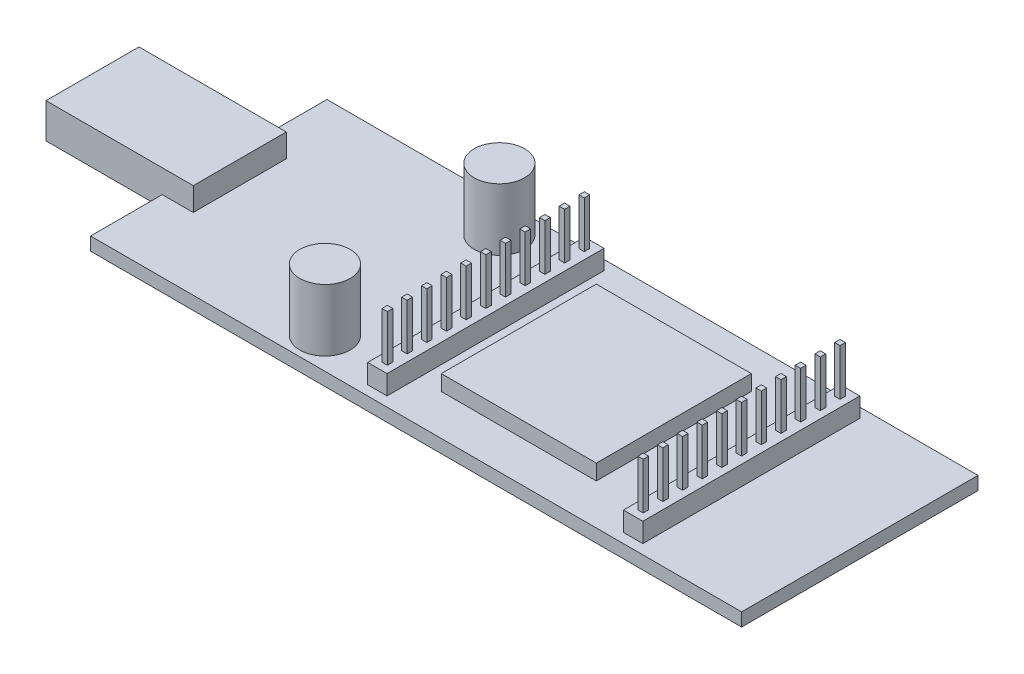
SolidWorks part; units mm, degrees
ref_plane "Front Plane" through (0, 0, 0) normal (0, 0, 1) x (1, 0, 0)
ref_plane "Top Plane" through (0, 0, 0) normal (0, 1, 0) x (1, 0, 0)
ref_plane "Right Plane" through (0, 0, 0) normal (1, 0, 0) x (0, 0, -1)
sketch "Sketch1" plane through (0, 0, 0) normal (0, 1, 0) x (1, 0, 0)
  line L1 (-42, 15.25) -> (42, 15.25)
  line L2 (-42, 15.25) -> (-42, -15.25)
  line L3 (-42, -15.25) -> (42, -15.25)
  line L4 (42, 15.25) -> (42, -15.25)
  line L5 (-42, 15.25) -> (42, -15.25) construction
  line L6 (-42, -15.25) -> (42, 15.25) construction
  point P0 (0, 0)
  dimension "D1" = 84
  dimension "D2" = 30.5
extrude "Boss-Extrude1" add sketch "Sketch1" along normal blind 1.7
sketch "Sketch2" plane through (0, 1.7, 0) normal (0, 1, 0) x (1, 0, 0)
  line L0 (-42, 0) -> (-53.9187, 0) construction
  line L1 (-42, 15.25) -> (-42, -15.25) construction
  line L3 (-57, -6) -> (-38, -6)
  line L4 (-57, -6) -> (-57, 6)
  line L5 (-57, 6) -> (-38, 6)
  line L6 (-38, -6) -> (-38, 6)
  line L7 (-57, -6) -> (-38, 6) construction
  line L8 (-57, 6) -> (-38, -6) construction
  point P5 (-47.5, 0)
  dimension "D1" = 12
  dimension "D2" = 19
  dimension "D3" = 15
extrude "Boss-Extrude2" add sketch "Sketch2" along normal blind 3 and the other way blind 1.5
sketch "Sketch3" plane through (0, 1.7, 0) normal (0, 1, 0) x (1, 0, 0)
  line L0 (0, 0) -> (42, 0) construction
  line L1 (42, -15.25) -> (42, 15.25) construction
  line L3 (-2, -10) -> (18, -10)
  line L4 (-2, -10) -> (-2, 10)
  line L5 (-2, 10) -> (18, 10)
  line L6 (18, -10) -> (18, 10)
  line L7 (-2, -10) -> (18, 10) construction
  line L8 (-2, 10) -> (18, -10) construction
  point P5 (8, 0)
  dimension "D1" = 20
  dimension "D2" = 20
  dimension "D3" = 34
extrude "Boss-Extrude3" add sketch "Sketch3" along normal blind 2
sketch "Sketch4" plane through (0, 0, 0) normal (0, -1, 0) x (1, 0, 0)
  line L1 (-36.2017, 11.8652) -> (-30.5739, 11.8652)
  line L2 (-36.2017, 11.8652) -> (-36.2017, 6.894)
  line L3 (-36.2017, 6.894) -> (-30.5739, 6.894)
  line L4 (-30.5739, 11.8652) -> (-30.5739, 6.894)
  line L5 (-36.2017, 11.8652) -> (-30.5739, 6.894) construction
  line L6 (-36.2017, 6.894) -> (-30.5739, 11.8652) construction
  line L7 (-26.1186, -0.7973) -> (-16.4576, -0.7973)
  line L8 (-26.1186, -0.7973) -> (-26.1186, -5.2995)
  line L9 (-26.1186, -5.2995) -> (-16.4576, -5.2995)
  line L10 (-16.4576, -0.7973) -> (-16.4576, -5.2995)
  line L11 (-26.1186, -0.7973) -> (-16.4576, -5.2995) construction
  line L12 (-26.1186, -5.2995) -> (-16.4576, -0.7973) construction
  line L13 (10.8372, 12.4749) -> (20.3106, 12.4749)
  line L14 (10.8372, 12.4749) -> (10.8372, 3.8456)
  line L15 (10.8372, 3.8456) -> (20.3106, 3.8456)
  line L16 (20.3106, 12.4749) -> (20.3106, 3.8456)
  line L17 (10.8372, 12.4749) -> (20.3106, 3.8456) construction
  line L18 (10.8372, 3.8456) -> (20.3106, 12.4749) construction
  line L19 (4.8342, -0.8911) -> (14.7766, -0.8911)
  line L20 (4.8342, -0.8911) -> (4.8342, -8.3948)
  line L21 (4.8342, -8.3948) -> (14.7766, -8.3948)
  line L22 (14.7766, -0.8911) -> (14.7766, -8.3948)
  line L23 (4.8342, -0.8911) -> (14.7766, -8.3948) construction
  line L24 (4.8342, -8.3948) -> (14.7766, -0.8911) construction
  point P0 (-33.3878, 9.3796)
  point P5 (-21.2881, -3.0484)
  point P10 (15.5739, 8.1603)
  point P15 (9.8054, -4.6429)
extrude "Boss-Extrude4" add sketch "Sketch4" along normal blind 2
sketch "Sketch5" plane through (0, 1.7, 0) normal (0, 1, 0) x (1, 0, 0)
  line L0 (-15.7541, 15.25) -> (-15.7541, -15.25) construction
  line L1 (42, 15.25) -> (-42, 15.25) construction
  line L2 (-42, -15.25) -> (42, -15.25) construction
  line L3 (-19.0369, 0) -> (-11.9553, 0) construction
  circle A0 centre (-15.7541, 11.25) radius 3.25
  circle A1 centre (-15.7541, -11.25) radius 3.25
  dimension "D1" = 6.5
  dimension "D2" = 4
extrude "Boss-Extrude5" add sketch "Sketch5" along normal blind 8
sketch "Sketch6" plane through (0, 1.7, 0) normal (0, 1, 0) x (1, 0, 0)
  line L0 (-41.6888, 0) -> (42, 0) construction
  line L1 (42, -15.25) -> (42, 15.25) construction
  line L3 (-7.5, -14) -> (-5, -14)
  line L4 (-7.5, -14) -> (-7.5, 14)
  line L5 (-7.5, 14) -> (-5, 14)
  line L6 (-5, -14) -> (-5, 14)
  line L7 (-7.5, -14) -> (-5, 14) construction
  line L8 (-7.5, 14) -> (-5, -14) construction
  line L9 (25.5, -14) -> (28, -14)
  line L10 (25.5, -14) -> (25.5, 14)
  line L11 (25.5, 14) -> (28, 14)
  line L12 (28, -14) -> (28, 14)
  line L13 (25.5, -14) -> (28, 14) construction
  line L14 (25.5, 14) -> (28, -14) construction
  point P4 (-6.25, 0)
  point P9 (26.75, 0)
  dimension "D1" = 2.5
  dimension "D2" = 2.5
  dimension "D3" = 28
  dimension "D4" = 28
  dimension "D5" = 14
  dimension "D6" = 47
extrude "Boss-Extrude6" add sketch "Sketch6" along normal blind 2.5
sketch "Sketch7" plane through (0, 4.2, 0) normal (0, 1, 0) x (1, 0, 0)
  line L0 (-6.25, 14) -> (-6.25, -14) construction
  line L1 (-5, 14) -> (-7.5, 14) construction
  line L2 (-7.5, -14) -> (-5, -14) construction
  line L3 (-7.5, 0) -> (-5, 0) construction
  line L4 (-7.5, 14) -> (-7.5, -14) construction
  line L5 (-5, -14) -> (-5, 14) construction
  line L6 (-6.6, 2.89) -> (-6.6, 2.19)
  line L7 (-6.6, 0.35) -> (-5.9, 0.35)
  line L8 (-6.6, 0.35) -> (-6.6, -0.35)
  line L9 (-6.6, -0.35) -> (-5.9, -0.35)
  line L10 (-5.9, 0.35) -> (-5.9, -0.35)
  line L11 (-6.6, 0.35) -> (-5.9, -0.35) construction
  line L12 (-6.6, -0.35) -> (-5.9, 0.35) construction
  line L13 (-6.6, 2.89) -> (-5.9, 2.89)
  line L14 (-5.9, 2.89) -> (-5.9, 2.19)
  line L15 (-6.6, 2.19) -> (-5.9, 2.19)
  line L16 (-6.6, 5.43) -> (-6.6, 4.73)
  line L17 (-6.6, 5.43) -> (-5.9, 5.43)
  line L18 (-5.9, 5.43) -> (-5.9, 4.73)
  line L19 (-6.6, 4.73) -> (-5.9, 4.73)
  line L20 (-6.6, 7.97) -> (-6.6, 7.27)
  line L21 (-6.6, 7.97) -> (-5.9, 7.97)
  line L22 (-5.9, 7.97) -> (-5.9, 7.27)
  line L23 (-6.6, 7.27) -> (-5.9, 7.27)
  line L24 (-6.6, 10.51) -> (-6.6, 9.81)
  line L25 (-6.6, 10.51) -> (-5.9, 10.51)
  line L26 (-5.9, 10.51) -> (-5.9, 9.81)
  line L27 (-6.6, 9.81) -> (-5.9, 9.81)
  line L28 (-6.6, 13.05) -> (-6.6, 12.35)
  line L29 (-6.6, 13.05) -> (-5.9, 13.05)
  line L30 (-5.9, 13.05) -> (-5.9, 12.35)
  line L31 (-6.6, 12.35) -> (-5.9, 12.35)
  line L32 (-6.6, -2.19) -> (-6.6, -2.89)
  line L33 (-6.6, -2.19) -> (-5.9, -2.19)
  line L34 (-5.9, -2.19) -> (-5.9, -2.89)
  line L35 (-6.6, -2.89) -> (-5.9, -2.89)
  line L36 (-6.6, -4.73) -> (-6.6, -5.43)
  line L37 (-6.6, -4.73) -> (-5.9, -4.73)
  line L38 (-5.9, -4.73) -> (-5.9, -5.43)
  line L39 (-6.6, -5.43) -> (-5.9, -5.43)
  line L40 (-6.6, -7.27) -> (-6.6, -7.97)
  line L41 (-6.6, -7.27) -> (-5.9, -7.27)
  line L42 (-5.9, -7.27) -> (-5.9, -7.97)
  line L43 (-6.6, -7.97) -> (-5.9, -7.97)
  line L44 (-6.6, -9.81) -> (-6.6, -10.51)
  line L45 (-6.6, -9.81) -> (-5.9, -9.81)
  line L46 (-5.9, -9.81) -> (-5.9, -10.51)
  line L47 (-6.6, -10.51) -> (-5.9, -10.51)
  line L48 (-6.6, -12.35) -> (-6.6, -13.05)
  line L49 (-6.6, -12.35) -> (-5.9, -12.35)
  line L50 (-5.9, -12.35) -> (-5.9, -13.05)
  line L51 (-6.6, -13.05) -> (-5.9, -13.05)
  line L52 (27.1, 2.89) -> (27.1, 2.19)
  line L53 (26.4, 10.51) -> (26.4, 9.81)
  line L54 (26.4, -12.35) -> (26.4, -13.05)
  line L55 (26.4, -2.19) -> (26.4, -2.89)
  line L56 (26.4, 0.35) -> (27.1, -0.35) construction
  line L57 (26.4, 7.97) -> (27.1, 7.97)
  line L58 (26.4, 13.05) -> (26.4, 12.35)
  line L59 (26.4, 0.35) -> (27.1, 0.35)
  line L60 (26.4, -0.35) -> (27.1, -0.35)
  line L61 (27.1, 13.05) -> (27.1, 12.35)
  line L62 (27.1, -12.35) -> (27.1, -13.05)
  line L63 (27.1, 0.35) -> (27.1, -0.35)
  line L64 (26.4, -5.43) -> (27.1, -5.43)
  line L65 (26.4, -10.51) -> (27.1, -10.51)
  line L66 (26.4, 2.89) -> (26.4, 2.19)
  line L67 (26.4, 2.89) -> (27.1, 2.89)
  line L68 (26.4, -9.81) -> (27.1, -9.81)
  line L69 (26.4, -12.35) -> (27.1, -12.35)
  line L70 (27.1, 7.97) -> (27.1, 7.27)
  line L71 (26.4, 9.81) -> (27.1, 9.81)
  line L72 (27.1, -4.73) -> (27.1, -5.43)
  line L73 (27.1, -7.27) -> (27.1, -7.97)
  line L74 (26.4, 0.35) -> (26.4, -0.35)
  line L75 (26.4, 5.43) -> (27.1, 5.43)
  line L76 (27.1, -2.19) -> (27.1, -2.89)
  line L77 (26.4, -4.73) -> (26.4, -5.43)
  line L78 (26.4, 2.19) -> (27.1, 2.19)
  line L79 (26.4, 13.05) -> (27.1, 13.05)
  line L80 (26.4, -0.35) -> (27.1, 0.35) construction
  line L81 (26.4, 10.51) -> (27.1, 10.51)
  line L82 (26.4, -2.19) -> (27.1, -2.19)
  line L83 (27.1, 10.51) -> (27.1, 9.81)
  line L84 (26.4, -7.27) -> (26.4, -7.97)
  line L85 (26.4, -9.81) -> (26.4, -10.51)
  line L86 (26.4, 7.97) -> (26.4, 7.27)
  line L87 (26.75, 14) -> (26.75, -14) construction
  line L88 (26.4, 4.73) -> (27.1, 4.73)
  line L89 (26.4, 7.27) -> (27.1, 7.27)
  line L90 (26.4, -4.73) -> (27.1, -4.73)
  line L91 (27.1, -9.81) -> (27.1, -10.51)
  line L92 (27.1, 5.43) -> (27.1, 4.73)
  line L93 (26.4, 12.35) -> (27.1, 12.35)
  line L94 (26.4, 5.43) -> (26.4, 4.73)
  line L95 (26.4, -2.89) -> (27.1, -2.89)
  line L96 (26.4, -7.97) -> (27.1, -7.97)
  line L97 (26.4, -7.27) -> (27.1, -7.27)
  line L98 (26.4, -13.05) -> (27.1, -13.05)
  point P12 (-6.25, 0)
  point P59 (26.75, 0)
  dimension "D1" = 0.7
  dimension "D2" = 0.7
  dimension "D3" = 6
extrude "Boss-Extrude7" add sketch "Sketch7" along normal blind 6
